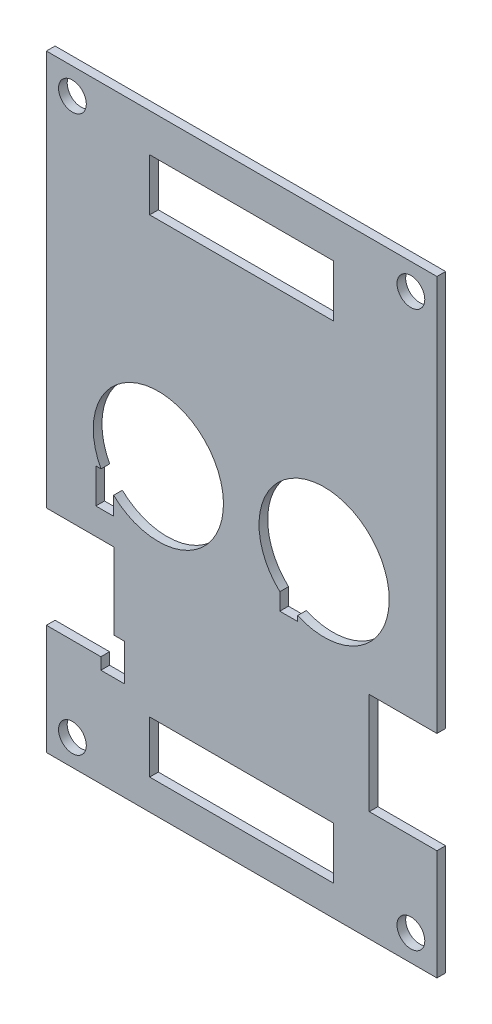
SolidWorks part; units mm, degrees
ref_plane "Front Plane" through (0, 0, 0) normal (0, 0, 1) x (1, 0, 0)
ref_plane "Top Plane" through (0, 0, 0) normal (0, 1, 0) x (1, 0, 0)
ref_plane "Right Plane" through (0, 0, 0) normal (1, 0, 0) x (0, 0, -1)
sketch "Sketch1" plane through (0, 0, 0) normal (0, 0, 1) x (1, 0, 0)
  line L0 (20.7342, -15.2835) -> (20.7342, -27.9835)
  line L1 (-24.2658, 42.0165) -> (20.7342, 42.0165)
  line L2 (-24.2658, 42.0165) -> (-24.2658, -3.5835)
  line L3 (-24.2658, -27.9835) -> (20.7342, -27.9835)
  line L4 (20.7342, 42.0165) -> (20.7342, -3.5835)
  line L5 (-24.2658, -3.5835) -> (-16.4658, -3.5835)
  line L7 (-24.2658, -15.2835) -> (-17.9858, -15.2835)
  line L8 (-16.4658, -3.5835) -> (-16.4658, -12.3835)
  line L9 (20.7342, -3.5835) -> (12.9342, -3.5835)
  line L10 (-24.2658, -15.2835) -> (-24.2658, -27.9835)
  line L11 (20.7342, -15.2835) -> (12.9342, -15.2835)
  line L12 (12.9342, -3.5835) -> (12.9342, -15.2835)
  line L13 (-15.2658, -12.3835) -> (-16.4658, -12.3835)
  line L14 (-15.2658, -12.3835) -> (-15.2658, -16.6335)
  line L15 (-15.2658, -16.6335) -> (-17.9858, -16.6335)
  line L16 (-17.9858, -15.2835) -> (-17.9858, -16.6335)
  circle A0 centre (-21.2658, 39.0165) radius 1.6
  circle A1 centre (17.7342, 39.0165) radius 1.6
  circle A2 centre (-21.2658, -24.9835) radius 1.6
  circle A3 centre (17.7342, -24.9835) radius 1.6
  dimension "D3" = 3
  dimension "D4" = 3
  dimension "D5" = 3
  dimension "D6" = 3
  dimension "D7" = 12.7
  dimension "D1" = 45
  dimension "D2" = 70
  dimension "D8" = 24.4
  dimension "D9" = 7.8
  dimension "D10" = 7.8
  dimension "D11" = 6.28
  dimension "D12" = 9
  dimension "D13" = 11.35
  dimension "D14" = 15.6
extrude "Boss-Extrude1" add sketch "Sketch1" along normal blind 1
sketch "Sketch2" plane through (0, 0, 1) normal (0, 0, 1) x (1, 0, 0)
  line L0 (-24.2658, -27.9835) -> (20.7342, -27.9835) construction
  line L1 (-24.2658, 42.0165) -> (-24.2658, -3.5835) construction
  circle A0 centre (-11.3658, 7.0165) radius 7.5
  circle A1 centre (7.7342, 7.0165) radius 7.5
  dimension "D1" = 35
  dimension "D2" = 12.9
  dimension "D3" = 35
  dimension "D4" = 32
sketch "Sketch4" plane through (0, 0, 1) normal (0, 0, 1) x (1, 0, 0)
  line L0 (-24.2658, 42.0165) -> (-24.2658, -3.5835) construction
  line L1 (-12.3658, -24.4835) -> (8.8342, -24.4835)
  line L2 (-12.3658, -24.4835) -> (-12.3658, -18.4835)
  line L3 (-12.3658, -18.4835) -> (8.8342, -18.4835)
  line L4 (8.8342, -24.4835) -> (8.8342, -18.4835)
  line L5 (-24.2658, -27.9835) -> (20.7342, -27.9835) construction
  line L7 (-12.3658, 31.6165) -> (8.8342, 31.6165)
  line L8 (-12.3658, 31.6165) -> (-12.3658, 37.6165)
  line L9 (-12.3658, 37.6165) -> (8.8342, 37.6165)
  line L10 (8.8342, 31.6165) -> (8.8342, 37.6165)
  dimension "D1" = 6
  dimension "D2" = 21.2
  dimension "D3" = 11.9
  dimension "D4" = 3.5
  dimension "D5" = 6
  dimension "D6" = 11.9
  dimension "D7" = 59.6
  dimension "D8" = 21.2
sketch "Sketch5" plane through (0, 0, 1) normal (0, 0, 1) x (1, 0, 0)
  line L0 (-24.2658, -27.9835) -> (20.7342, -27.9835) construction
  line L1 (-18.5658, 3.4665) -> (-16.5158, 3.4665)
  line L2 (-18.5658, 3.4665) -> (-18.5658, -0.5335)
  line L3 (-18.5658, -0.5335) -> (-16.5158, -0.5335)
  line L4 (-16.5158, 3.4665) -> (-16.5158, -0.5335)
  line L5 (-24.2658, 42.0165) -> (-24.2658, -3.5835) construction
  line L7 (2.6342, 3.5665) -> (4.6842, 3.5665)
  line L8 (2.6342, 3.5665) -> (2.6342, -0.4335)
  line L9 (2.6342, -0.4335) -> (4.6842, -0.4335)
  line L10 (4.6842, 3.5665) -> (4.6842, -0.4335)
  dimension "D1" = 4
  dimension "D2" = 2.05
  dimension "D3" = 27.45
  dimension "D4" = 5.7
  dimension "D5" = 2.05
  dimension "D6" = 4
  dimension "D7" = 27.55
  dimension "D8" = 26.9
extrude "Cut-Extrude1" cut sketch "Sketch5" against normal blind 4
extrude "Cut-Extrude2" cut sketch "Sketch4" against normal blind 4
extrude "Cut-Extrude3" cut sketch "Sketch2" against normal blind 4
